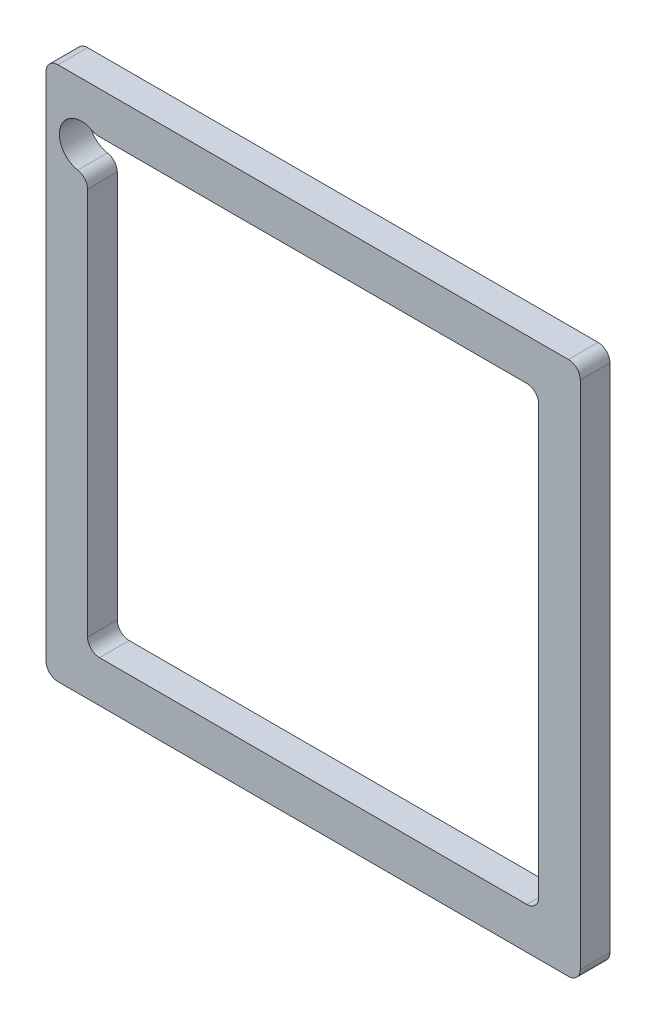
SolidWorks part; units mm, degrees
ref_plane "Front Plane" through (0, 0, 0) normal (0, 0, 1) x (1, 0, 0)
ref_plane "Top Plane" through (0, 0, 0) normal (0, 1, 0) x (1, 0, 0)
ref_plane "Right Plane" through (0, 0, 0) normal (1, 0, 0) x (0, 0, -1)
sketch "Sketch1" plane through (0, 0, 0) normal (0, 0, 1) x (1, 0, 0)
  line L0 (-54.61, -57.15) -> (54.61, -57.15)
  line L1 (-57.15, -54.61) -> (-57.15, 54.61)
  line L2 (-54.61, 57.15) -> (54.61, 57.15)
  line L3 (57.15, -54.61) -> (57.15, 54.61)
  line L4 (-57.15, -57.15) -> (-56.4061, -56.4061) construction
  line L5 (-57.15, 0) -> (57.15, 0) construction
  line L6 (52.6065, -56.1713) -> (57.15, -57.15) construction
  line L7 (0, 57.15) -> (0, -57.15) construction
  line L8 (-45.72, -48.26) -> (11.6497, -48.26)
  line L9 (-48.26, -45.72) -> (-48.26, -0.7521)
  line L10 (48.26, -17.5136) -> (48.26, 45.72)
  line L11 (-48.26, -48.26) -> (48.26, 48.26) construction
  line L12 (-48.26, 48.26) -> (33.8079, -33.8079) construction
  line L13 (12.3175, 48.26) -> (45.72, 48.26)
  line L14 (48.26, -17.5136) -> (48.26, -48.26) construction
  line L15 (11.6497, -48.26) -> (48.26, -48.26) construction
  line L16 (-48.26, -0.7521) -> (-48.26, 37.2588)
  line L17 (-45.9239, 48.26) -> (12.3175, 48.26)
  line L19 (11.6497, -48.26) -> (45.72, -48.26)
  line L20 (48.26, -17.5136) -> (48.26, -45.72)
  arc A0 (-54.61, -57.15) -> (-57.15, -54.61) centre (-54.61, -54.61) cw
  arc A1 (54.61, -57.15) -> (57.15, -54.61) centre (54.61, -54.61) ccw
  arc A2 (54.61, 57.15) -> (57.15, 54.61) centre (54.61, 54.61) cw
  arc A3 (-57.15, 54.61) -> (-54.61, 57.15) centre (-54.61, 54.61) cw
  arc A9 (-45.72, -48.26) -> (-48.26, -45.72) centre (-45.72, -45.72) cw
  arc A12 (45.72, 48.26) -> (48.26, 45.72) centre (45.72, 45.72) cw
  arc A16 (45.72, -48.26) -> (48.26, -45.72) centre (45.72, -45.72) ccw
  arc A18 (-47.1782, 48.5913) -> (-50.3583, 39.7601) centre (-49.53, 44.45) ccw
  arc A19 (-45.9239, 48.26) -> (-47.1782, 48.5913) centre (-45.9239, 50.8) cw
  arc A20 (-48.26, 37.2588) -> (-50.3583, 39.7601) centre (-50.8, 37.2588) ccw
  point P0 (0, 0)
  point P1 (0, 0)
  point P6 (-48.26, 39.86)
  point P16 (0, 0)
  dimension "D1" = 2.54
  dimension "D4" = 9.525
  dimension "D5" = 2.54
  dimension "D2" = 7.62
  dimension "D3" = 12.7
  dimension "D7" = 109.22
  dimension "D8" = 109.22
  dimension "D10" = 96.52
extrude "Boss-Extrude1" add sketch "Sketch1" along normal mid plane 6.35
